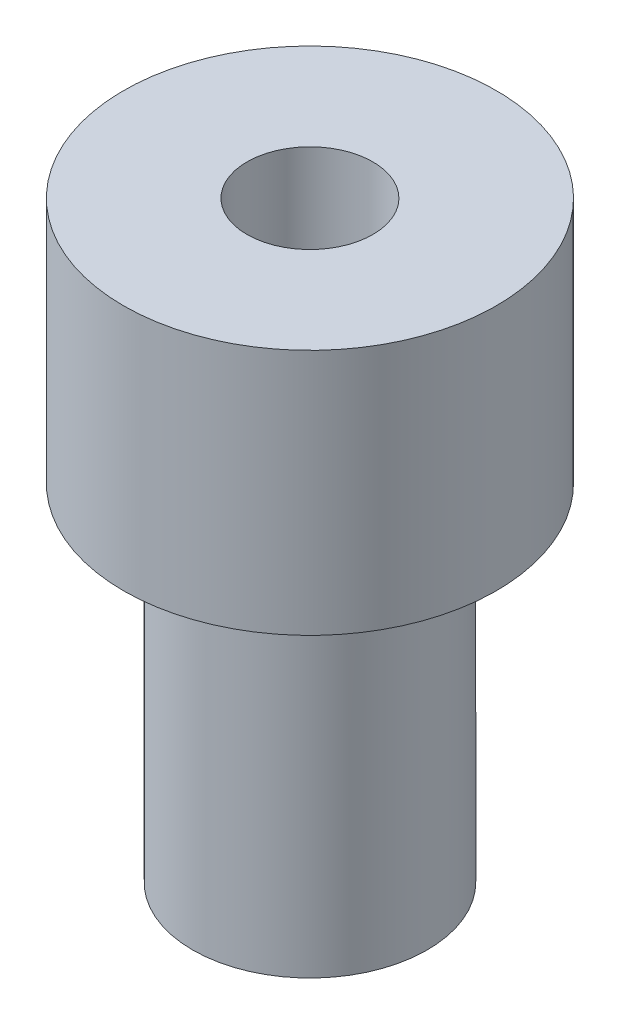
SolidWorks part; units mm, degrees
ref_plane "Front Plane" through (0, 0, 0) normal (0, 0, 1) x (1, 0, 0)
ref_plane "Top Plane" through (0, 0, 0) normal (0, 1, 0) x (1, 0, 0)
ref_plane "Right Plane" through (0, 0, 0) normal (1, 0, 0) x (0, 0, -1)
sketch "Sketch1" plane through (0, 0, 0) normal (0, 0, 1) x (1, 0, 0)
  line L0 (0, 5.1734) -> (0, -5.1734) construction
  line L8 (-2.55, 0) -> (-2.55, 24)
  line L9 (-2.55, 24) -> (-7.55, 24)
  line L10 (-7.55, 24) -> (-7.55, 14)
  line L11 (-7.55, 14) -> (-4.75, 14)
  line L12 (-4.75, 14) -> (-4.75, 0)
  line L13 (-4.75, 0) -> (-2.55, 0)
  point P4 (0, 0)
  dimension "D1" = 2.55
  dimension "D2" = 4.75
  dimension "D3" = 5
  dimension "D4" = 10
  dimension "D5" = 14
revolve "Revolve1" add sketch "Sketch1" angle 360 about L0
chamfer "Chamfer1" distance 0.4 angle 45 1 edges at (0, 14, 4.75)
